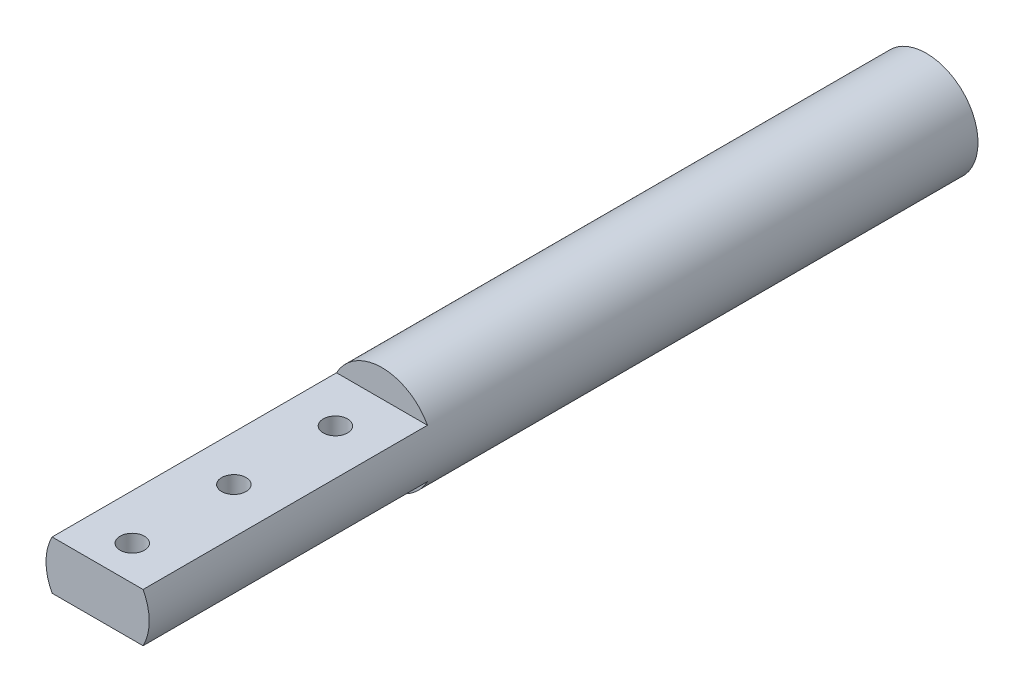
SolidWorks part; units mm, degrees
ref_plane "Front Plane" through (0, 0, 0) normal (0, 0, 1) x (1, 0, 0)
ref_plane "Top Plane" through (0, 0, 0) normal (0, 1, 0) x (1, 0, 0)
ref_plane "Right Plane" through (0, 0, 0) normal (1, 0, 0) x (0, 0, -1)
sketch "Sketch1" plane through (0, 0, 0) normal (0, 0, 1) x (1, 0, 0)
  circle A0 centre (0, 0) radius 6.35
  dimension "D1" = 12.7
extrude "Boss-Extrude1" add sketch "Sketch1" along normal mid plane 102
sketch "Sketch2" plane through (0, 0, 51) normal (0, 0, 1) x (1, 0, 0)
  line L0 (-5.5967, 3) -> (5.5967, 3)
  line L1 (-1000, 0) -> (49000, 0) construction
  line L2 (-5.5967, -3) -> (5.5967, -3)
  circle A0 centre (0, 0) radius 6.35 construction
  circle A1 centre (0, 0) radius 6.35
  dimension "D1" = 3
extrude "Cut-Extrude1" cut sketch "Sketch2" against normal blind 35
sketch "Sketch3" plane through (0, 3, 0) normal (0, 1, 0) x (1, 0, 0)
  circle A0 centre (0, -21.732) radius 1.5
  circle A1 centre (0, -34.232) radius 1.5
  circle A2 centre (0, -46.732) radius 1.5
  dimension "D1" = 3
  dimension "D2" = 3
extrude "Cut-Extrude2" cut sketch "Sketch3" against normal blind 15 from surface at 0 starting at face at (0, 3, 33.5)
